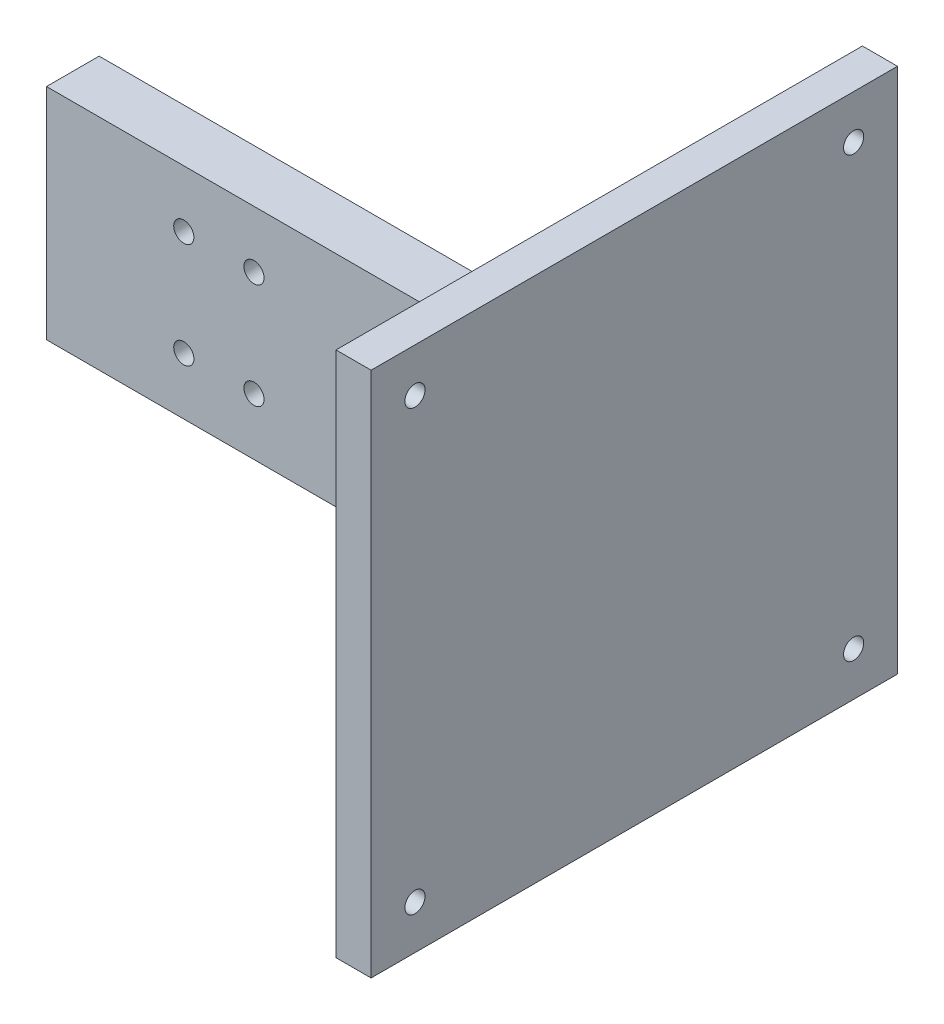
SolidWorks part; units mm, degrees
ref_plane "Front Plane" through (0, 0, 0) normal (0, 0, 1) x (1, 0, 0)
ref_plane "Top Plane" through (0, 0, 0) normal (0, 1, 0) x (1, 0, 0)
ref_plane "Right Plane" through (0, 0, 0) normal (1, 0, 0) x (0, 0, -1)
sketch "Sketch1" plane through (0, 0, 0) normal (0, 0, 1) x (1, 0, 0)
  line L1 (-30, 12.5) -> (30, 12.5)
  line L2 (-30, 12.5) -> (-30, -12.5)
  line L3 (-30, -12.5) -> (30, -12.5)
  line L4 (30, 12.5) -> (30, -12.5)
  line L5 (-30, 12.5) -> (30, -12.5) construction
  line L6 (-30, -12.5) -> (30, 12.5) construction
  point P0 (0, 0)
  dimension "D1" = 60
  dimension "D2" = 25
extrude "Boss-Extrude1" add sketch "Sketch1" along normal blind 6
sketch "Sketch4" plane through (0, 0, 0) normal (0, 0, -1) x (-1, 0, 0)
  line L4 (6.35, -6) -> (14.35, -6)
  line L5 (6.35, -6) -> (6.35, 6)
  line L6 (6.35, 6) -> (14.35, 6)
  line L7 (14.35, -6) -> (14.35, 6)
  line L8 (6.35, -6) -> (14.35, 6) construction
  line L9 (6.35, 6) -> (14.35, -6) construction
  circle A0 centre (6.35, 6) radius 2.1
  circle A1 centre (6.35, -6) radius 2.1
  circle A2 centre (14.35, -6) radius 2.1
  circle A3 centre (14.35, 6) radius 2.1
  point P1 (10.35, 0)
  dimension "D3" = 10.35
  dimension "D1" = 8
  dimension "D2" = 12
  dimension "D4" = 0
extrude "Cut-Extrude3" cut sketch "Sketch4" against normal blind 3 contours L6 A0 L5 | L5 A0 L6 | A3 L6 L7 | A3 L7 L6 | L4 A2 L7 | L7 A2 L4 | A1 L4 L5 | A1 L5 L4
sketch "Sketch5" plane through (0, 0, 3) normal (0, 0, -1) x (-1, 0, 0)
  circle A0 centre (6.35, 6) radius 1.15
  circle A1 centre (14.35, 6) radius 1.15
  circle A2 centre (14.35, -6) radius 1.15
  circle A3 centre (6.35, -6) radius 1.15
  circle A4 centre (14.35, -6) radius 2.1 construction
  circle A6 centre (14.35, 6) radius 2.1 construction
extrude "Cut-Extrude4" cut sketch "Sketch5" against normal through all contours A0 | A1 | A2 | A3
ref_plane "Plane1" through (-30, -12.5, 0) normal (1, 0, 0) x (0, 0, -1)
sketch "Sketch6" plane through (-30, -12.5, 0) normal (1, 0, 0) x (0, 0, -1)
sketch "Sketch7" plane through (30, 0, 0) normal (1, 0, 0) x (0, 0, -1)
  line L1 (27, -30) -> (-33, -30)
  line L2 (27, -30) -> (27, 30)
  line L3 (27, 30) -> (-33, 30)
  line L4 (-33, -30) -> (-33, 30)
  line L5 (27, -30) -> (-33, 30) construction
  line L6 (27, 30) -> (-33, -30) construction
  point P0 (-3, 0)
  dimension "D1" = 60
  dimension "D2" = 60
extrude "Boss-Extrude2" add sketch "Sketch7" along normal blind 4
sketch "Sketch8" plane through (34, 0, 0) normal (1, 0, 0) x (0, 0, -1)
  line L0 (17, -20) -> (27, -30)
  line L1 (27, -30) -> (17, -30)
  line L2 (27, -30) -> (27, -20)
  line L3 (27, -20) -> (17, -20)
  line L4 (17, -30) -> (17, -20)
  circle A0 centre (22, -25) radius 1.15
  circle A1 centre (-28, -25) radius 1.15
  circle A2 centre (-28, 25) radius 1.15
  circle A3 centre (22, 25) radius 1.15
  point P9 (-3, 0)
  point P19 (-3, 0)
  dimension "D3" = 2.3
  dimension "D1" = 10
  dimension "D2" = 10
  dimension "D4" = 4
extrude "Cut-Extrude5" cut sketch "Sketch8" against normal blind 10 contours A1 | A2 | L0 A0 | L0 A0 | A3
sketch "Sketch9" plane through (30, 0, 0) normal (-1, 0, 0) x (0, 0, 1)
  line L0 (33, -30) -> (-27, 30)
  line L1 (28, 22.5751) -> (30.1, 23.7876)
  line L2 (30.1, 23.7876) -> (30.1, 26.2124)
  line L3 (30.1, 26.2124) -> (28, 27.4249)
  line L4 (28, 27.4249) -> (25.9, 26.2124)
  line L5 (25.9, 26.2124) -> (25.9, 23.7876)
  line L6 (25.9, 23.7876) -> (28, 22.5751)
  line L7 (3, 0) -> (3, -20.4325)
  line L8 (3, 0) -> (23.1818, 0)
  line L9 (25.9, -23.7876) -> (28, -22.5751)
  line L10 (25.9, -26.2124) -> (25.9, -23.7876)
  line L11 (28, -27.4249) -> (25.9, -26.2124)
  line L12 (30.1, -26.2124) -> (28, -27.4249)
  line L13 (30.1, -23.7876) -> (30.1, -26.2124)
  line L14 (28, -22.5751) -> (30.1, -23.7876)
  line L15 (-22, -22.5751) -> (-24.1, -23.7876)
  line L16 (-19.9, -23.7876) -> (-22, -22.5751)
  line L17 (-19.9, -26.2124) -> (-19.9, -23.7876)
  line L18 (-22, -27.4249) -> (-19.9, -26.2124)
  line L19 (-24.1, -26.2124) -> (-22, -27.4249)
  line L20 (-24.1, -23.7876) -> (-24.1, -26.2124)
  line L21 (-24.1, 26.2124) -> (-22, 27.4249)
  line L22 (-22, 27.4249) -> (-19.9, 26.2124)
  line L23 (-19.9, 26.2124) -> (-19.9, 23.7876)
  line L24 (-19.9, 23.7876) -> (-22, 22.5751)
  line L25 (-22, 22.5751) -> (-24.1, 23.7876)
  line L26 (-24.1, 23.7876) -> (-24.1, 26.2124)
  circle A0 centre (28, 25) radius 2.1 construction
  point P13 (3, 0)
  circle M15 centre (28, 25) radius 1.15
  circle M16 centre (-22, -25) radius 1.15
  circle M17 centre (-22, 25) radius 1.15
  circle M18 centre (28, -25) radius 1.15
  dimension "D1" = 4.2
extrude "Cut-Extrude6" cut sketch "Sketch9" against normal blind 2 contours L5 L6 L1 L2 L3 L4 M15 | L14 L9 L0 L12 L13 M18 | L12 L0 L9 L10 L11 M18 | L15 L20 L19 L18 L17 L16 M16 | L24 L23 L22 L21 L0 M17 | L26 L25 L24 L0 L21 M17
